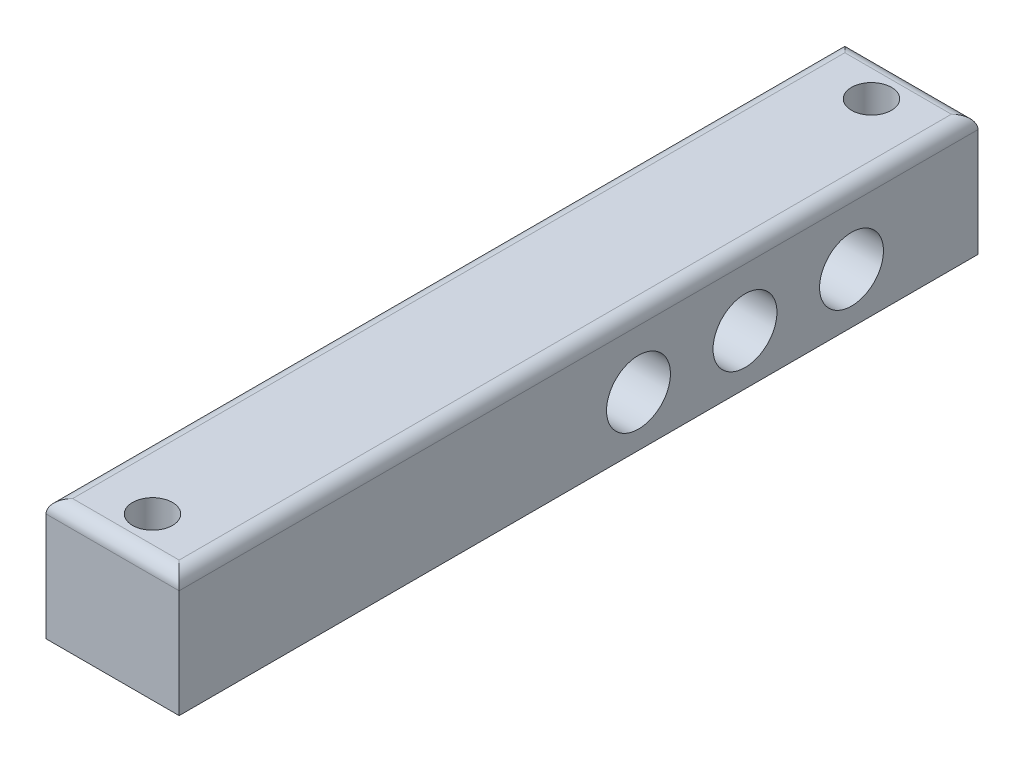
SolidWorks part; units mm, degrees
ref_plane "Alzado" through (0, 0, 0) normal (0, 0, 1) x (1, 0, 0)
ref_plane "Planta" through (0, 0, 0) normal (0, 1, 0) x (1, 0, 0)
ref_plane "Vista lateral" through (0, 0, 0) normal (1, 0, 0) x (0, 0, -1)
sketch "Croquis1" plane through (0, 0, 0) normal (0, 1, 0) x (1, 0, 0)
  line L1 (-10, 0) -> (0, 0)
  line L2 (-10, 0) -> (-10, -60)
  line L3 (-10, -60) -> (0, -60)
  line L4 (0, 0) -> (0, -60)
  dimension "D1" = 60
  dimension "D2" = 10
  dimension "D3" = 0
  dimension "D4" = 0
extrude "Saliente-Extruir1" add sketch "Croquis1" along normal blind 9.12
sketch "Croquis2" plane through (-10, 0, 0) normal (-1, 0, 0) x (0, 0, 1)
  line L0 (0, 0) -> (60, 0) construction
  line L1 (60, 9.12) -> (60, 0) construction
  circle A0 centre (17.5, 3.79) radius 2.4
  circle A1 centre (9.5, 3.79) radius 2.4
  circle A2 centre (25.5, 3.79) radius 2.4
  dimension "D1" = 3.79
  dimension "D2" = 42.5
  dimension "D3" = 4.8
  dimension "D4" = 4.8
  dimension "D5" = 8
  dimension "D6" = 8
  dimension "D7" = 4.8
  dimension "D8" = 3.79
  dimension "D9" = 3.79
extrude "Cortar-Extruir1" cut sketch "Croquis2" against normal through all
sketch "Croquis4" plane through (0, 9.12, 0) normal (0, 1, 0) x (1, 0, 0)
  line L0 (0, 0) -> (-10, 0) construction
  line L1 (-10, 0) -> (-10, -60) construction
  line L2 (-10, -60) -> (0, -60) construction
  circle A0 centre (-5, -3) radius 1.5
  circle A1 centre (-5, -57) radius 1.5
  dimension "D1" = 3
  dimension "D2" = 3
  dimension "D3" = 5
  dimension "D4" = 3
  dimension "D5" = 5
  dimension "D6" = 3
extrude "Cortar-Extruir2" cut sketch "Croquis4" against normal through all
fillet "Redondeo1" radius 1 4 edges at (-5, 9.12, 60) (-5, 9.12, 0) (0, 9.12, 30) (-10, 9.12, 30)
